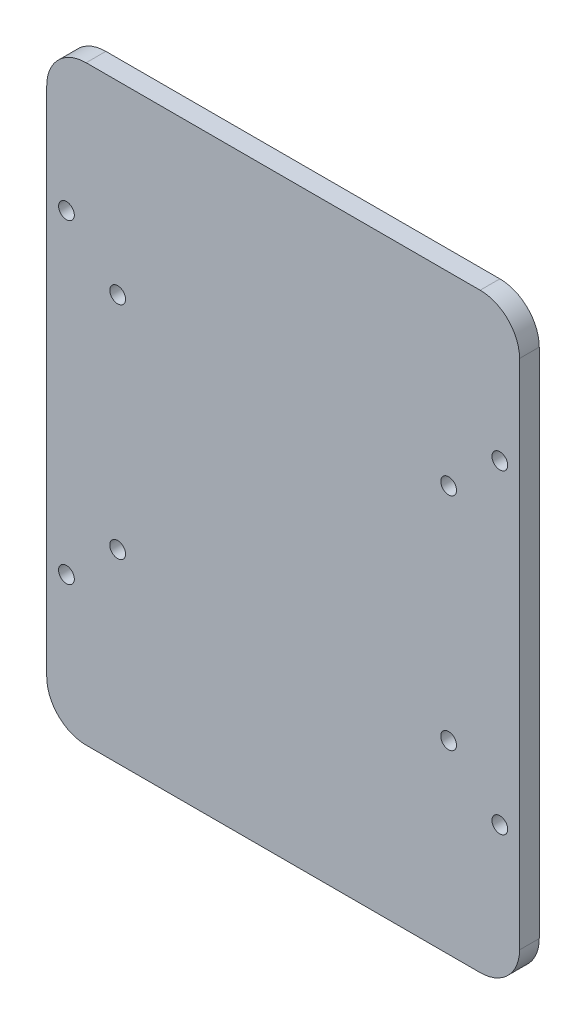
SolidWorks part; units mm, degrees
ref_plane "前视基准面" through (0, 0, 0) normal (0, 0, 1) x (1, 0, 0)
ref_plane "上视基准面" through (0, 0, 0) normal (0, 1, 0) x (1, 0, 0)
ref_plane "右视基准面" through (0, 0, 0) normal (1, 0, 0) x (0, 0, -1)
sketch "草图1" plane through (0, 0, 0) normal (0, 0, 1) x (1, 0, 0)
  line L0 (0, 0) -> (0, 150)
  line L1 (0, 150) -> (120, 150)
  line L2 (120, 150) -> (120, 0)
  line L3 (120, 0) -> (0, 0)
  dimension "D1" = 150
  dimension "D2" = 120
extrude "凸台-拉伸1" add sketch "草图1" along normal blind 5
fillet "圆角1" radius 10 4 edges at (0, 0, 2.5) (120, 0, 2.5) (120, 150, 2.5) (0, 150, 2.5)
ref_plane "基准面1" through (60, 0, 0) normal (-1, 0, 0) x (0, 0, 1)
ref_plane "基准面2" through (0, 75, 0) normal (0, -1, 0) x (-1, 0, 0)
sketch "草图2" plane through (0, 0, 5) normal (0, 0, 1) x (1, 0, 0)
  line L0 (0, 140) -> (0, 10) construction
  line L1 (-2.75, 75) -> (2.75, 75) construction
  circle A0 centre (18, 47) radius 2
  circle A1 centre (5, 35) radius 2
  dimension "D1" = 18
  dimension "D3" = 40
  dimension "D4" = 5
  dimension "D2" = 28
extrude "切除-拉伸1" cut sketch "草图2" against normal blind 10
mirror "镜向1" about plane through (0, 75, 0) normal (0, -1, 0) of "切除-拉伸1"
mirror "镜向2" about plane through (60, 0, 0) normal (-1, 0, 0) of "镜向1", "切除-拉伸1"
